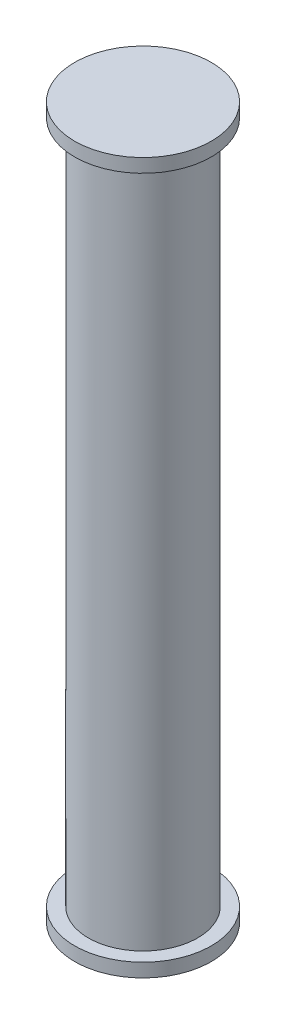
SolidWorks part; units mm, degrees
material "Cast Carbon Steel"
ref_plane "Front Plane" through (0, 0, 0) normal (0, 0, 1) x (1, 0, 0)
ref_plane "Top Plane" through (0, 0, 0) normal (0, 1, 0) x (1, 0, 0)
ref_plane "Right Plane" through (0, 0, 0) normal (1, 0, 0) x (0, 0, -1)
sketch "Sketch1" plane through (0, 0, 0) normal (0, 1, 0) x (1, 0, 0)
  circle A0 centre (0, 0) radius 10.16
  dimension "D1" = 20.32
extrude "Boss-Extrude1" add sketch "Sketch1" along normal mid plane 132.08
sketch "Sketch2" plane through (0, 66.04, 0) normal (0, 1, 0) x (1, 0, 0)
  circle A0 centre (0, 0) radius 12.7
  dimension "D1" = 25.4
extrude "Boss-Extrude2" add sketch "Sketch2" against normal blind 2.54
sketch "Sketch3" plane through (0, -66.04, 0) normal (0, -1, 0) x (1, 0, 0)
  circle A0 centre (0, 0) radius 12.7
  dimension "D1" = 25.4
extrude "Boss-Extrude3" add sketch "Sketch3" against normal blind 2.54
